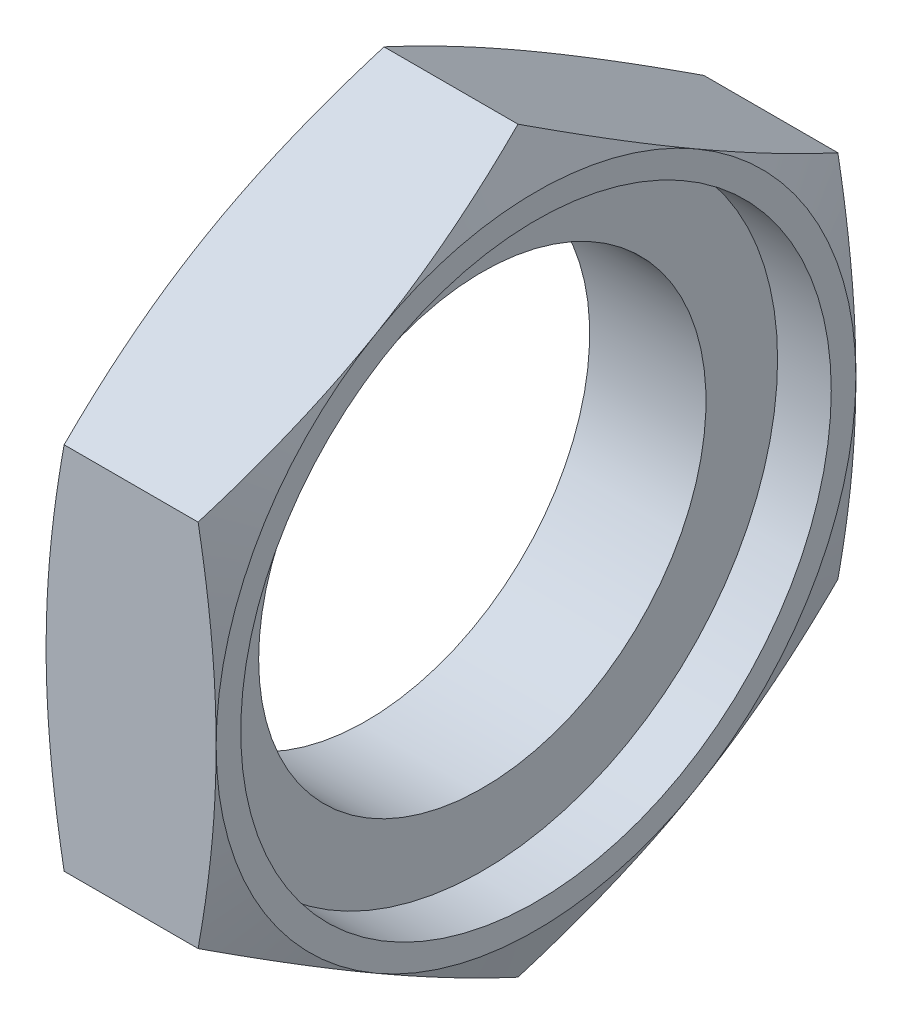
SolidWorks part; units mm, degrees
material "AISI 1020"
ref_plane "Plano superior" through (0, 0, 0) normal (0, 0, 1) x (1, 0, 0)
ref_plane "Plano frontal" through (0, 0, 0) normal (0, 1, 0) x (1, 0, 0)
ref_plane "Plano direito" through (0, 0, 0) normal (1, 0, 0) x (0, 0, -1)
sketch "Esboço1" plane through (0, 0, 0) normal (1, 0, 0) x (0, 0, -1)
  line L0 (0, 0) -> (0, 17.4672) construction
  line L1 (14.3, 8.2561) -> (0, 16.5122)
  line L2 (0, 16.5122) -> (-14.3, 8.2561)
  line L3 (-14.3, 8.2561) -> (-14.3, -8.2561)
  line L4 (-14.3, -8.2561) -> (0, -16.5122)
  line L5 (0, -16.5122) -> (14.3, -8.2561)
  line L6 (14.3, -8.2561) -> (14.3, 8.2561)
  line L7 (-14.3, 8.2561) -> (0, 0) construction
  circle A0 centre (0, 0) radius 14.3 construction
  circle A1 centre (0, 0) radius 10
  dimension "D1" = 28.6
  dimension "D2" = 20
  dimension "D3" = 60
extrude "Ressalto-extrusão1" add sketch "Esboço1" along normal blind 7.6
cosmetic thread "Representação de rosca2" parameters "D2"=22
sketch "Esboço3" plane through (0, 0, 0) normal (-1, 0, 0) x (0, 0, 1)
  circle A0 centre (0, 0) radius 14.3
sketch "Esboço4" plane through (7.6, 0, 0) normal (1, 0, 0) x (0, 0, -1)
  circle A0 centre (0, 0) radius 14.3
hole_wizard "Furo1" positions "Esboço5" profile "Esboço6" legacy
sketch "Esboço5" plane through (7.6, 0, 0) normal (1, 0, 0) x (0, 0, -1)
  point P0 (0, 0)
  point P3 (0, 0)
sketch "Esboço6" plane through (7.6, 0, 0) normal (0, 1, 0) x (0, 0, -1)
  line L0 (0, 0) -> (0, 2.4)
  line L1 (0, 2.4) -> (13.2, 2.4)
  line L2 (13.2, 2.4) -> (13.2, 0)
  line L3 (13.2, 0) -> (0, 0)
  line L4 (0, 110) -> (0, -10) construction
  dimension "Diameter" = 26.4
  dimension "Depth" = 2.4
sketch "Esboço7" plane through (7.6, 0, 0) normal (1, 0, 0) x (0, 0, -1)
  circle A0 centre (0, 0) radius 14.3
extrude "Corte-extrusão1" cut sketch "Esboço7" against normal blind 13 draft 70 flip side to cut
sketch "Esboço8" plane through (0, 0, 0) normal (-1, 0, 0) x (0, 0, 1)
  circle A0 centre (0, 0) radius 14.3
extrude "Corte-extrusão2" cut sketch "Esboço8" against normal blind 13 draft 70 flip side to cut
